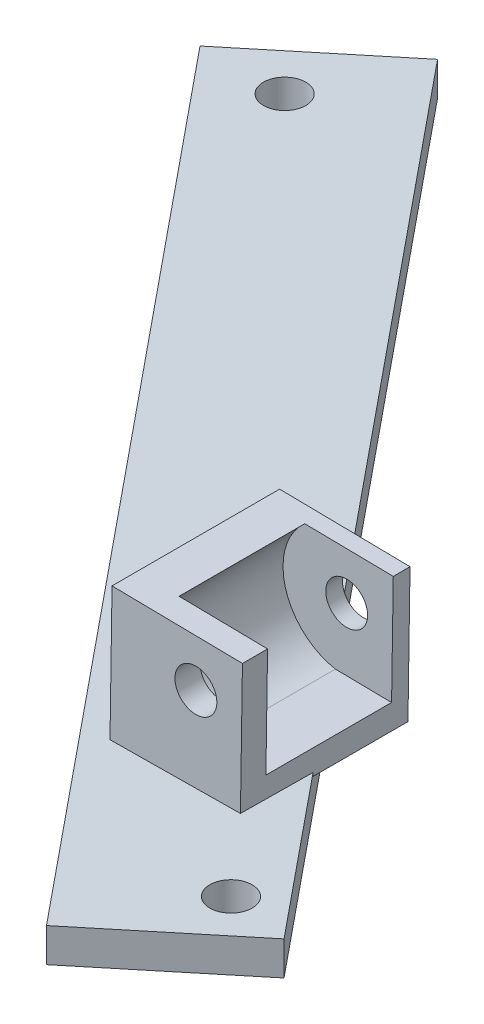
SolidWorks part; units mm, degrees
ref_plane "Front Plane" through (0, 0, 0) normal (0, 0, 1) x (1, 0, 0)
ref_plane "Top Plane" through (0, 0, 0) normal (0, 1, 0) x (1, 0, 0)
ref_plane "Right Plane" through (0, 0, 0) normal (1, 0, 0) x (0, 0, -1)
sketch "Sketch1" plane through (0, 0, 0) normal (0, 0, 1) x (1, 0, 0)
  line L0 (-620.8374, 110.7203) -> (-621.1503, 90.2249)
  line L1 (-604.7125, 110.4741) -> (-634.2525, 110.9251) construction
  line L2 (-621.1503, 90.2249) -> (-640.9147, 90.5267)
  line L3 (-640.9147, 90.5267) -> (-640.6018, 111.0221)
  line L4 (-640.6018, 111.0221) -> (-620.8374, 110.7203)
  line L5 (-606.4491, 93.8109) -> (-629.5989, 94.1643) construction
  line L6 (-606.4491, 93.8109) -> (-629.5989, 94.1643)
  arc A0 (-634.2525, 110.9251) -> (-634.4712, 96.6012) centre (-627.8931, 103.6644) ccw construction
  arc A1 (-634.4712, 96.6012) -> (-629.5989, 94.1643) centre (-627.8931, 103.6644) ccw construction
  arc A2 (-634.2525, 110.9251) -> (-634.4712, 96.6012) centre (-627.8931, 103.6644) ccw
  arc A3 (-634.4712, 96.6012) -> (-629.5989, 94.1643) centre (-627.8931, 103.6644) ccw
  dimension "D1" = 3.81
  dimension "D2" = 6.35
  dimension "D3" = 19.7667
extrude "Boss-Extrude1" add sketch "Sketch1" against normal blind 21.59 contours A3 A2 L4 L3 L2 L0 L6
sketch "Sketch2" plane through (0, 0, -19.05) normal (0, 0, -1) x (-1, 0, 0)
  line L0 (621.0921, 94.0345) -> (620.8374, 110.7203)
  line L1 (604.6203, 110.4727) -> (634.2525, 110.9251) construction
  line L2 (620.8374, 110.7203) -> (634.2525, 110.9251)
  line L3 (621.0921, 94.0345) -> (629.5989, 94.1643) construction
  line L4 (621.0921, 94.0345) -> (629.5989, 94.1643)
  line L5 (621.0921, 94.0345) -> (629.5989, 94.1643)
  circle A0 centre (627.8931, 103.6644) radius 3.175 construction
  arc A1 (629.5989, 94.1643) -> (634.2525, 110.9251) centre (627.8931, 103.6644) ccw construction
  circle A2 centre (627.8931, 103.6644) radius 3.175
  arc A3 (629.5989, 94.1643) -> (634.2525, 110.9251) centre (627.8931, 103.6644) ccw
  circle M6 centre (627.8931, 103.6644) radius 3.175
  line M7 (604.4767, 96.1432) -> (634.4712, 96.6012)
  arc M8 (634.4712, 96.6012) -> (634.2525, 110.9251) centre (627.8931, 103.6644) ccw
  line M9 (634.2525, 110.9251) -> (604.6203, 110.4727)
extrude "Boss-Extrude3" add sketch "Sketch2" along normal up to surface (2.54 mm away) contours L0 M7 M8 M9 M6 | L4 A3 L0 M7 up to face at (-632.1463, 98.2392, -21.59)
sketch "Sketch3" plane through (0, 0, 0) normal (0, 0, 1) x (1, 0, 0)
  line L0 (-640.6018, 111.0221) -> (-620.8374, 110.7203)
  line L1 (-620.8374, 110.7203) -> (-621.1503, 90.2249)
  line L2 (-621.1503, 90.2249) -> (-640.9147, 90.5267)
  line L3 (-640.9147, 90.5267) -> (-640.6018, 111.0221)
  circle A0 centre (-627.8931, 103.6644) radius 3.175
  dimension "D1" = 6.35
extrude "Boss-Extrude4" add sketch "Sketch3" along normal blind 3.81 contours L3 L0 L1 L2 | A0
ref_plane "Plane1" through (-1.0096, 97.2566, -1.0889) normal (-0.0104, 0.9999, -0.0112) x (0.9999, 0.0104, -0.0001)
sketch "Sketch4" plane through (-1.0096, 97.2566, -1.0889) normal (-0.0104, 0.9999, -0.0112) x (0.9999, 0.0104, -0.0001)
  line L0 (-726.1965, 95.0872) -> (-619.8166, -34.5745)
  line L5 (-619.8166, -34.5745) -> (-600.0384, -18.3477)
  line L6 (-600.0384, -18.3477) -> (-706.4183, 111.314)
  line L7 (-706.4183, 111.314) -> (-726.1965, 95.0872)
  circle A1 centre (-713.3679, 95.0872) radius 3.175
  circle A2 centre (-609.7559, -16.6729) radius 3.175
  point P2 (0, 0)
  point P5 (-734.2412, 95.0872)
  point P7 (-597.0072, -23.6322)
  point P8 (-699.6449, 116.1058)
  point P14 (0, 0)
  point P15 (-595.3129, -23.6348)
  point P16 (-592.9888, -23.5487)
  point P17 (-705.337, 109.8523)
  point P18 (0, 0)
  point P19 (0, 0)
  point P20 (-623.2542, -43.841)
  point P21 (0, 0)
  point P22 (-726.8378, 88.9031)
  point P23 (0, 0)
  point P24 (0, 0)
  point P25 (-730.258, 95.0872)
  point P26 (-731.113, 92.1096)
  point P27 (0, 0)
  point P28 (-594.7317, -24.6055)
  point P29 (-615.8943, -39.3552)
  point P30 (-726.1965, 95.0872)
  point P31 (-597.5106, -19.0476)
  dimension "D7" = 7.4584
  dimension "D9" = 6.35
  dimension "D10" = 6.35
  dimension "D6" = 8.137
  dimension "D2" = 0
  dimension "D3" = 180
  dimension "D4" = 90
  dimension "D5" = 9.9178
  dimension "D8" = 19.1327
  dimension "D11" = 15.6651
extrude "Boss-Extrude5" add sketch "Sketch4" against normal blind 5.08
